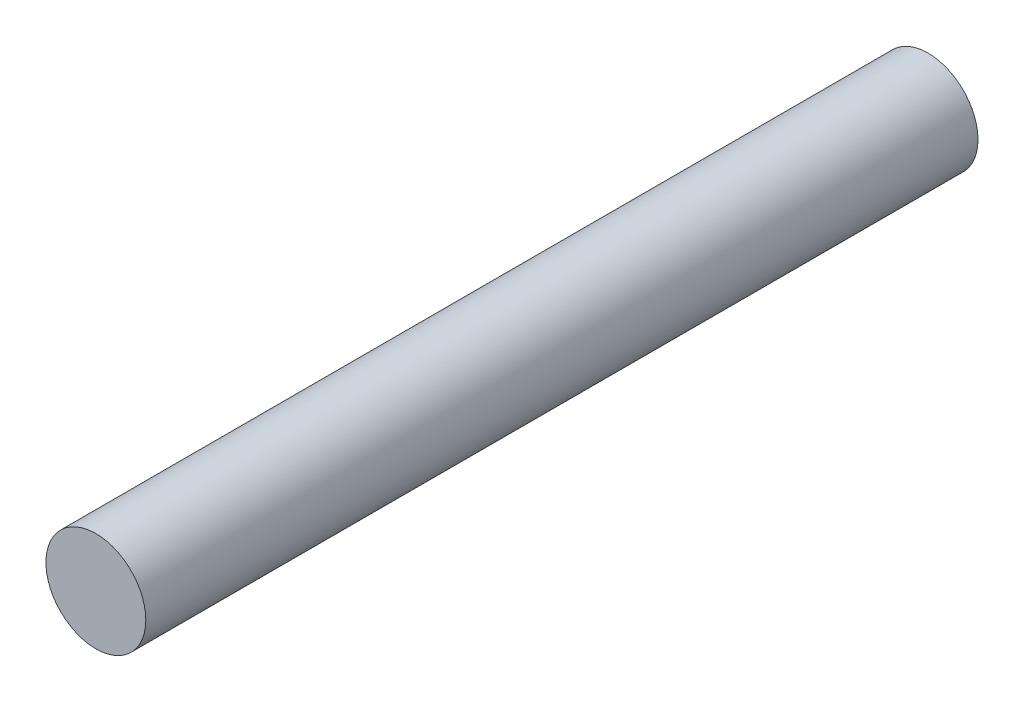
SolidWorks part; units mm, degrees
ref_plane "Plano frontal" through (0, 0, 0) normal (0, 0, 1) x (1, 0, 0)
ref_plane "Plano superior" through (0, 0, 0) normal (0, 1, 0) x (1, 0, 0)
ref_plane "Plano direito" through (0, 0, 0) normal (1, 0, 0) x (0, 0, -1)
sketch "Esboço1" plane through (0, 0, 0) normal (0, 0, 1) x (1, 0, 0)
  circle A0 centre (0, 0) radius 3
  dimension "D1" = 6
extrude "Ressalto-extrusão1" add sketch "Esboço1" along normal blind 50
